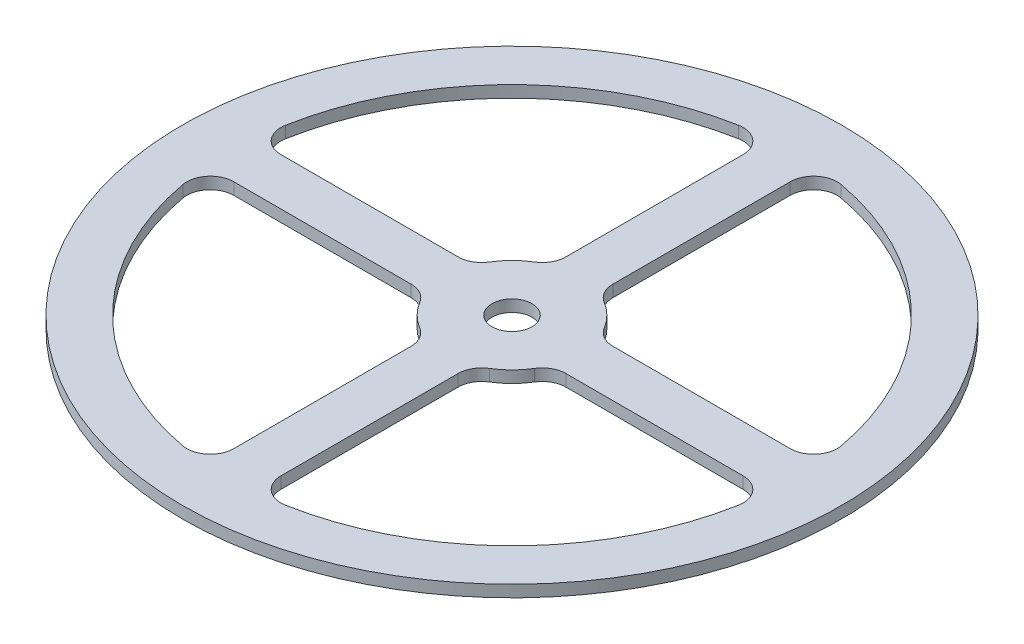
SolidWorks part; units mm, degrees
ref_plane "正面" through (0, 0, 0) normal (0, 0, 1) x (1, 0, 0)
ref_plane "平面" through (0, 0, 0) normal (0, 1, 0) x (1, 0, 0)
ref_plane "右側面" through (0, 0, 0) normal (1, 0, 0) x (0, 0, -1)
sketch "ｽｹｯﾁ1" plane through (0, 0, 0) normal (0, 1, 0) x (1, 0, 0)
  line L0 (-140, 0) -> (0, 0) construction
  line L1 (0, 0) -> (0, 140) construction
  line L2 (-108.1665, 10) -> (-32.8976, 10)
  line L3 (10, 108.1665) -> (10, 32.8976)
  line L4 (108.1665, 10) -> (32.8976, 10)
  line L5 (-10, 108.1665) -> (-10, 32.8976)
  line L6 (108.1665, -10) -> (32.8976, -10)
  line L7 (10, -108.1665) -> (10, -32.8976)
  line L8 (-10, -108.1665) -> (-10, -32.8976)
  line L9 (-108.1665, -10) -> (-32.8976, -10)
  circle A0 centre (0, 0) radius 140
  circle A1 centre (0, 0) radius 8.5
  arc A2 (-21.8182, 117.9999) -> (-117.9999, 21.8182) centre (0, 0) ccw
  arc A3 (-14.8052, 24.3527) -> (-24.3527, 14.8052) centre (0, 0) ccw
  circle A4 centre (0, 0) radius 120 construction
  circle A5 centre (0, 0) radius 28.5 construction
  arc A6 (-21.8182, 117.9999) -> (-10, 108.1665) centre (-20, 108.1665) cw
  arc A7 (-10, 32.8976) -> (-14.8052, 24.3527) centre (-20, 32.8976) cw
  arc A8 (-32.8976, 10) -> (-24.3527, 14.8052) centre (-32.8976, 20) ccw
  arc A9 (-108.1665, 10) -> (-117.9999, 21.8182) centre (-108.1665, 20) cw
  arc A10 (24.3527, 14.8052) -> (14.8052, 24.3527) centre (0, 0) ccw
  arc A11 (10, 32.8976) -> (14.8052, 24.3527) centre (20, 32.8976) ccw
  arc A12 (32.8976, 10) -> (24.3527, 14.8052) centre (32.8976, 20) cw
  arc A13 (10, 108.1665) -> (21.8182, 117.9999) centre (20, 108.1665) cw
  arc A14 (117.9999, 21.8182) -> (21.8182, 117.9999) centre (0, 0) ccw
  arc A15 (117.9999, 21.8182) -> (108.1665, 10) centre (108.1665, 20) cw
  arc A16 (14.8052, -24.3527) -> (24.3527, -14.8052) centre (0, 0) ccw
  arc A17 (32.8976, -10) -> (24.3527, -14.8052) centre (32.8976, -20) ccw
  arc A18 (10, -32.8976) -> (14.8052, -24.3527) centre (20, -32.8976) cw
  arc A19 (108.1665, -10) -> (117.9999, -21.8182) centre (108.1665, -20) cw
  arc A20 (21.8182, -117.9999) -> (117.9999, -21.8182) centre (0, 0) ccw
  arc A21 (21.8182, -117.9999) -> (10, -108.1665) centre (20, -108.1665) cw
  arc A22 (-24.3527, -14.8052) -> (-14.8052, -24.3527) centre (0, 0) ccw
  arc A23 (-10, -32.8976) -> (-14.8052, -24.3527) centre (-20, -32.8976) ccw
  arc A24 (-32.8976, -10) -> (-24.3527, -14.8052) centre (-32.8976, -20) cw
  arc A25 (-10, -108.1665) -> (-21.8182, -117.9999) centre (-20, -108.1665) cw
  arc A26 (-117.9999, -21.8182) -> (-21.8182, -117.9999) centre (0, 0) ccw
  arc A27 (-117.9999, -21.8182) -> (-108.1665, -10) centre (-108.1665, -20) cw
  dimension "D1" = 17
  dimension "D2" = 280
  dimension "D7" = 10
  dimension "D3" = 20
  dimension "D5" = 10
  dimension "D6" = 10
  dimension "D4" = 20
  dimension "D8" = 4
extrude "ﾎﾞｽ - 押し出し1" add sketch "ｽｹｯﾁ1" along normal blind 5
